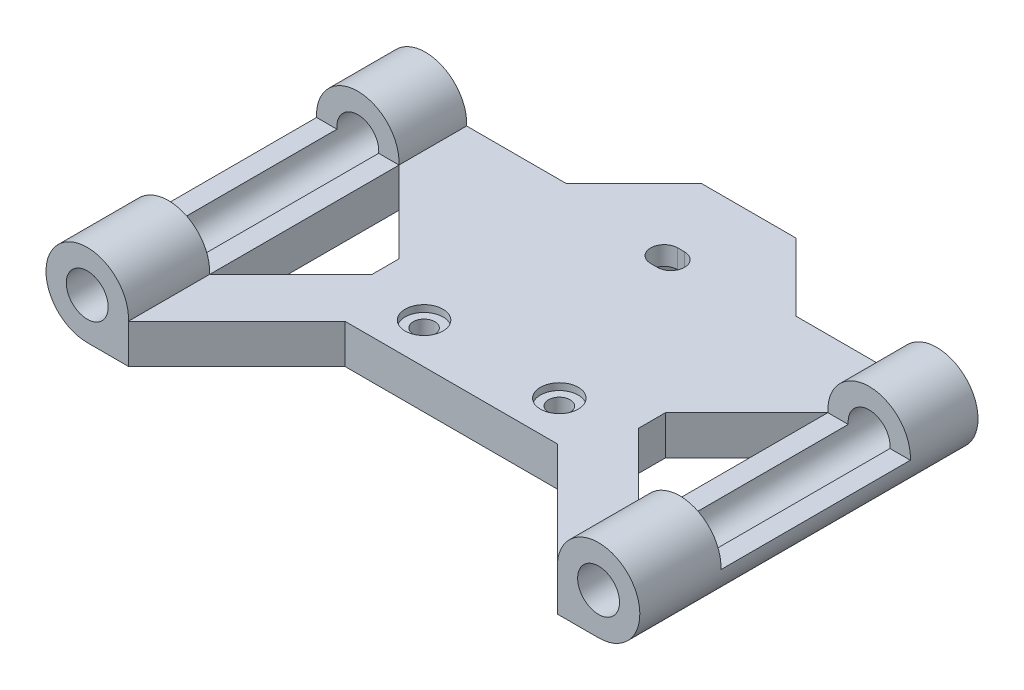
SolidWorks part; units mm, degrees
ref_plane "前视基准面" through (0, 0, 0) normal (0, 0, 1) x (1, 0, 0)
ref_plane "上视基准面" through (0, 0, 0) normal (0, 1, 0) x (1, 0, 0)
ref_plane "右视基准面" through (0, 0, 0) normal (1, 0, 0) x (0, 0, -1)
other "Configuration Table"
sketch "草图1" plane through (0, 0, 0) normal (0, 0, 1) x (1, 0, 0)
  line L0 (-46.6478, 2.4792) -> (-8.8478, 2.4792)
  line L1 (-43.6017, 5.3742) -> (-11.8938, 5.3742)
  line L2 (-37.4778, 5.3742) -> (-18.0178, 5.3742) construction
  circle A0 centre (-46.6478, 5.5292) radius 1.55
  circle A1 centre (-8.8478, 5.5292) radius 1.55
  circle A2 centre (-46.6478, 5.5292) radius 3.05
  circle A3 centre (-8.8478, 5.5292) radius 3.05
  dimension "D1" = 3.1
  dimension "D2" = 1.5
extrude "凸台-拉伸1" add sketch "草图1" along normal blind 25 contours A2 A0 | A3 L1 A2 L0 | A3 A1
sketch "草图2" plane through (0, 5.3742, 0) normal (0, 1, 0) x (1, 0, 0)
  line L0 (-19.2478, 0) -> (-24.2478, 5)
  line L1 (-43.6017, 0) -> (-11.8938, 0) construction
  line L2 (-24.2478, 5) -> (-31.2478, 5)
  line L4 (-31.2478, 5) -> (-36.2478, 0)
  line L6 (-27.7478, 17.7449) -> (-27.7478, -46.0927) construction
  line L9 (-43.5978, -25) -> (-43.5978, 0) construction
  line L10 (-11.8978, 0) -> (-11.8978, -25) construction
  line L11 (-36.2478, 0) -> (-19.2478, 0)
  dimension "D1" = 5
  dimension "D2" = 7
  dimension "D3" = 45
extrude "凸台-拉伸2" add sketch "草图2" against normal up to surface (2.895 mm away) up to face at (-27.7478, 2.4792, 12.5)
sketch "草图3" plane through (0, 5.3742, 0) normal (0, 1, 0) x (1, 0, 0)
  line L0 (-27.9978, -1) -> (-27.4978, -1) construction
  line L1 (-27.9978, 0) -> (-27.4978, 0)
  line L2 (-27.9978, -2) -> (-27.4978, -2)
  line L3 (-24.2478, 5) -> (-31.2478, 5) construction
  arc A0 (-27.9978, 0) -> (-27.9978, -2) centre (-27.9978, -1) ccw
  arc A1 (-27.4978, -2) -> (-27.4978, 0) centre (-27.4978, -1) ccw
  point P2 (-27.7478, -1)
  point P9 (0, 0)
  point P10 (-27.7478, 5)
  dimension "D1" = 1
  dimension "D2" = 0.5
  dimension "15" = 6
extrude "切除-拉伸1" cut sketch "草图3" against normal through all
sketch "草图5" plane through (0, 2.4792, 0) normal (0, -1, 0) x (-1, 0, 0)
  line L17 (29.8649, -1) -> (28.6813, 1.05)
  line L18 (28.6813, 1.05) -> (26.3142, 1.05)
  line L19 (26.3142, 1.05) -> (25.1306, -1)
  line L20 (25.1306, -1) -> (26.3142, -3.05)
  line L21 (26.3142, -3.05) -> (28.6813, -3.05)
  line L22 (28.6813, -3.05) -> (29.8649, -1)
  line L23 (30.3649, -1) -> (29.1813, 1.05)
  line L24 (29.1813, 1.05) -> (26.8142, 1.05)
  line L25 (26.8142, 1.05) -> (25.6306, -1)
  line L26 (25.6306, -1) -> (26.8142, -3.05)
  line L27 (26.8142, -3.05) -> (29.1813, -3.05)
  line L28 (29.1813, -3.05) -> (30.3649, -1)
  circle A4 centre (27.4978, -1) radius 2.05 construction
  arc A5 (27.4978, 0) -> (27.4978, -2) centre (27.4978, -1) ccw construction
  circle A6 centre (27.9978, -1) radius 2.05 construction
  arc A7 (27.9978, -2) -> (27.9978, 0) centre (27.9978, -1) ccw construction
  line M17 (27.4978, 0) -> (27.9978, 0)
  arc M18 (27.9978, 0) -> (27.9978, -2) centre (27.9978, -1) cw
  line M19 (27.9978, -2) -> (27.4978, -2)
  arc M20 (27.4978, -2) -> (27.4978, 0) centre (27.4978, -1) cw
  dimension "D1" = 4.1
extrude "切除-拉伸4" cut sketch "草图5" against normal blind 1.5 contours L26 L25 L18 L19 L20 L21 | L25 L26 L21 L22 L17 L18 M20 M17 M18 M19 | L27 L28 L23 L24 L17 L22
sketch "草图6" plane through (0, 5.3742, 0) normal (0, 1, 0) x (1, 0, 0)
  line L1 (-27.7478, -17.7348) -> (-27.7478, -33.5164) construction
  line L2 (-43.6017, -25) -> (-11.8938, -25) construction
  circle A0 centre (-32.7478, -14) radius 0.8
  circle A1 centre (-22.7478, -14) radius 0.8
  arc A3 (-27.4978, -2) -> (-27.4978, 0) centre (-27.4978, -1) ccw construction
  point P6 (-27.7478, -25)
  dimension "D2" = 1.6
  dimension "D3" = 13
  dimension "D1" = 10
extrude "切除-拉伸5" cut sketch "草图6" against normal through all
sketch "草图7" plane through (0, 5.3742, 0) normal (0, 1, 0) x (1, 0, 0)
  line L0 (-35.5978, -17) -> (-19.8938, -17)
  line L1 (-19.8938, -17) -> (-11.8938, -25)
  line L2 (-43.5978, -25) -> (-35.5978, -17)
  line L3 (-43.6017, -25) -> (-11.8938, -25) construction
  line L4 (-43.5978, -5) -> (-35.5978, -13)
  line L5 (-43.5978, -25) -> (-43.5978, 0) construction
  line L6 (-35.5978, -13) -> (-35.5978, -17)
  line L7 (-11.8978, -5) -> (-19.8938, -12.9961)
  line L8 (-11.8978, 0) -> (-11.8978, -25) construction
  line L9 (-19.8938, -12.9961) -> (-19.8938, -17)
  line L10 (-43.5978, -19) -> (-35.5978, -11)
  line L11 (-19.8938, -11.0039) -> (-11.8978, -19)
  line L12 (-27.7478, 9.0219) -> (-27.7478, -36.5602) construction
  line L13 (-24.2478, 5) -> (-31.2478, 5) construction
  line L14 (-43.6017, 0) -> (-36.2478, 0) construction
  line L15 (-43.5978, -5) -> (-43.5978, -19)
  line L16 (-11.8978, -5) -> (-11.8978, -19)
  line L17 (-37.5978, -11) -> (-37.5978, -13)
  line L18 (-17.8978, -11) -> (-17.8978, -13)
  circle A0 centre (-32.7478, -14) radius 0.8 construction
  point P26 (-27.7478, 5)
  dimension "D1" = 45
  dimension "D2" = 6
  dimension "D3" = 3
  dimension "D4" = 45
  dimension "D5" = 45
  dimension "D6" = 5
  dimension "D7" = 6
extrude "切除-拉伸6" cut sketch "草图7" against normal through all
sketch "草图9" plane through (-11.8978, 0, 0) normal (-1, 0, 0) x (0, 0, 1)
  line L0 (25, 3.9792) -> (25, 7.0792) construction
  line L1 (25, 3.9792) -> (25, 7.0792)
  line L2 (0, 8.5792) -> (0, 2.4792) construction
  line L3 (25, 3.9792) -> (0, 3.9792)
  line L4 (25, 3.9792) -> (25, 8.5792)
  line L5 (25, 8.5792) -> (0, 8.5792)
  line L6 (0, 3.9792) -> (0, 8.5792)
  line L7 (25, 8.5792) -> (0, 8.5792) construction
  line L8 (5, 5.3742) -> (19, 5.3742) construction
  line L9 (5, 5.3742) -> (19, 5.3742)
  line L12 (19, 5.3742) -> (5, 5.3742)
  line L13 (5, 5.3742) -> (5, 2.4792)
  line L14 (5, 2.4792) -> (19, 2.4792)
  line L15 (19, 2.4792) -> (19, 5.3742)
  line L17 (5, 8.5792) -> (5, 2.4792)
  line L18 (5, 2.4792) -> (19, 2.4792)
  line L19 (19, 2.4792) -> (19, 8.5792)
  line M5 (19, 5.3742) -> (5, 5.3742)
  dimension "D1" = 0
extrude "切除-拉伸9" cut sketch "草图9" against normal through all contours L19 L5 L17 M5
ref_plane "基准面1" through (-27.7478, 0, 0) normal (1, 0, 0) x (0, 0, -1)
mirror "镜向1" about plane through (-27.7478, 0, 0) normal (1, 0, 0) of "切除-拉伸9"
sketch "草图10" plane through (0, 5.3742, 0) normal (0, 1, 0) x (1, 0, 0)
  circle A0 centre (-22.7478, -14) radius 1.4
  circle A1 centre (-32.7478, -14) radius 1.4
  circle A2 centre (-22.7478, -14) radius 0.8 construction
  circle A3 centre (-32.7478, -14) radius 0.8 construction
  dimension "D1" = 2.8
extrude "切除-拉伸11" cut sketch "草图10" against normal blind 0.5
